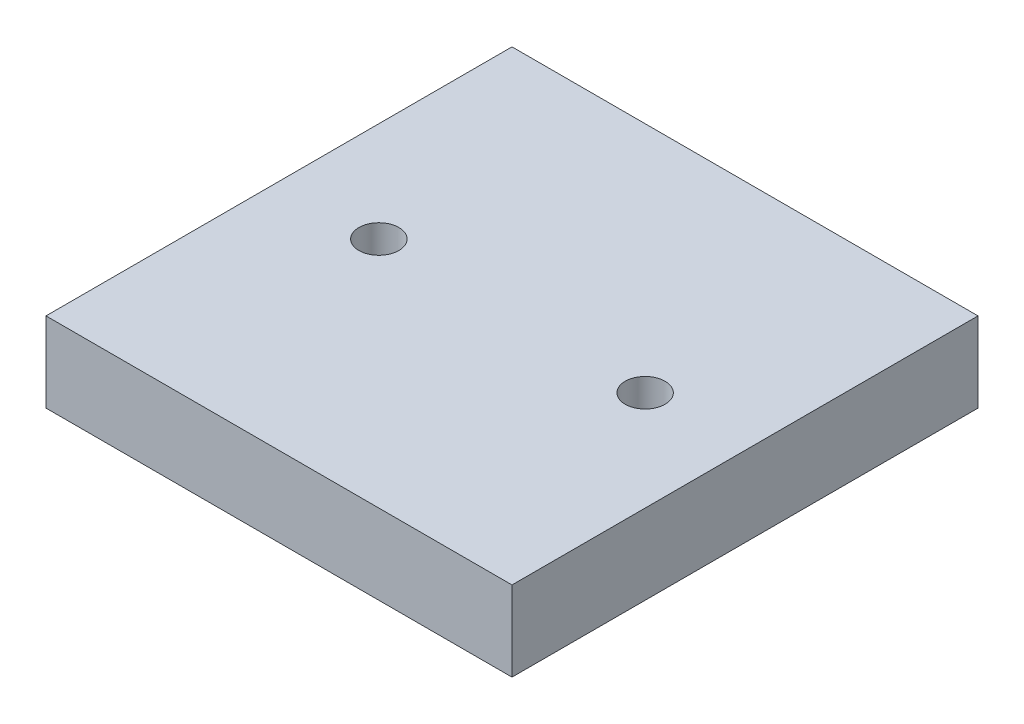
SolidWorks part; units mm, degrees
material "Beech"
ref_plane "Front Plane" through (0, 0, 0) normal (0, 0, 1) x (1, 0, 0)
ref_plane "Top Plane" through (0, 0, 0) normal (0, 1, 0) x (1, 0, 0)
ref_plane "Right Plane" through (0, 0, 0) normal (1, 0, 0) x (0, 0, -1)
sketch "Sketch1" plane through (0, 0, 0) normal (0, 1, 0) x (1, 0, 0)
  line L0 (-33.1245, 0) -> (35.7749, 0) construction
  line L1 (-35, -35) -> (35, -35)
  line L2 (-35, -35) -> (-35, 35)
  line L3 (-35, 35) -> (35, 35)
  line L4 (35, -35) -> (35, 35)
  line L5 (-35, -35) -> (35, 35) construction
  line L6 (-35, 35) -> (35, -35) construction
  circle A0 centre (-20, 0) radius 3
  circle A1 centre (20, 0) radius 3
  point P0 (0, 0)
  dimension "D3" = 6
  dimension "D4" = 6
  dimension "D5" = 20
  dimension "D6" = 20
  dimension "D1" = 70
  dimension "D2" = 70
extrude "Boss-Extrude1" add sketch "Sketch1" along normal blind 12
